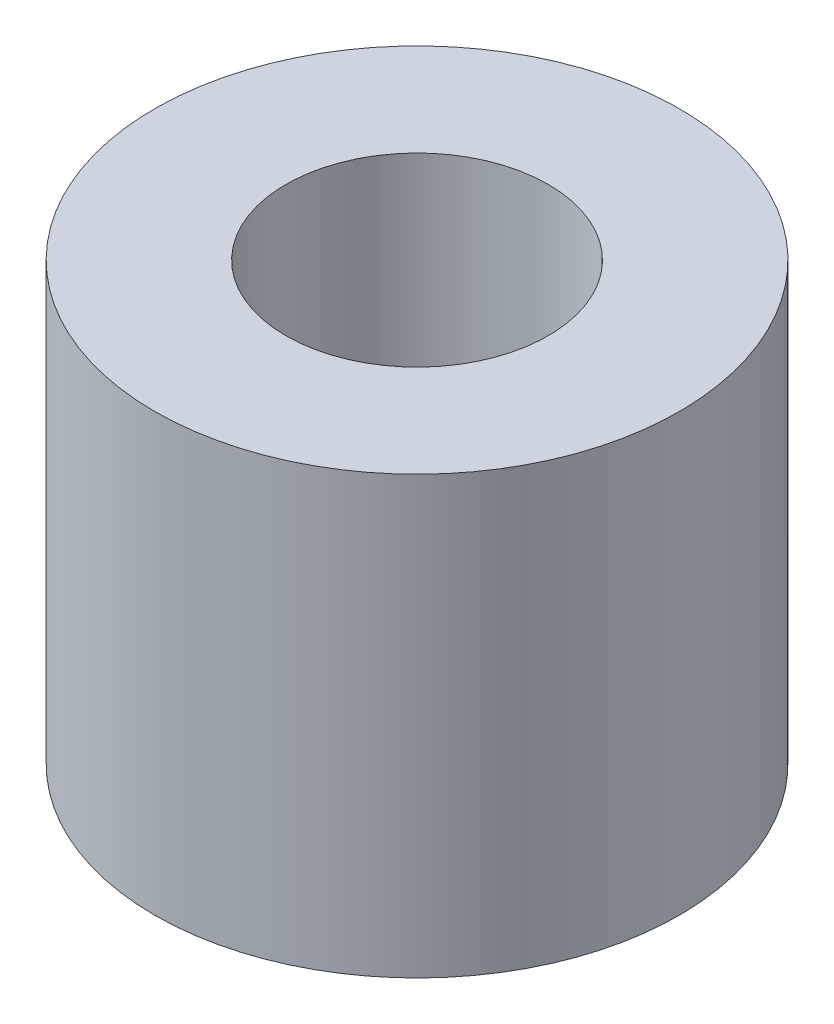
SolidWorks part; units mm, degrees
ref_plane "Front Plane" through (0, 0, 0) normal (0, 0, 1) x (1, 0, 0)
ref_plane "Top Plane" through (0, 0, 0) normal (0, 1, 0) x (1, 0, 0)
ref_plane "Right Plane" through (0, 0, 0) normal (1, 0, 0) x (0, 0, -1)
sketch "Sketch2" plane through (0, 0, 0) normal (0, 1, 0) x (1, 0, 0)
  circle A0 centre (0, -0.0185) radius 3
  circle A1 centre (0, -0.0185) radius 1.5
  dimension "D1" = 6
  dimension "D2" = 3
extrude "Boss-Extrude1" add sketch "Sketch2" along normal blind 4.99
